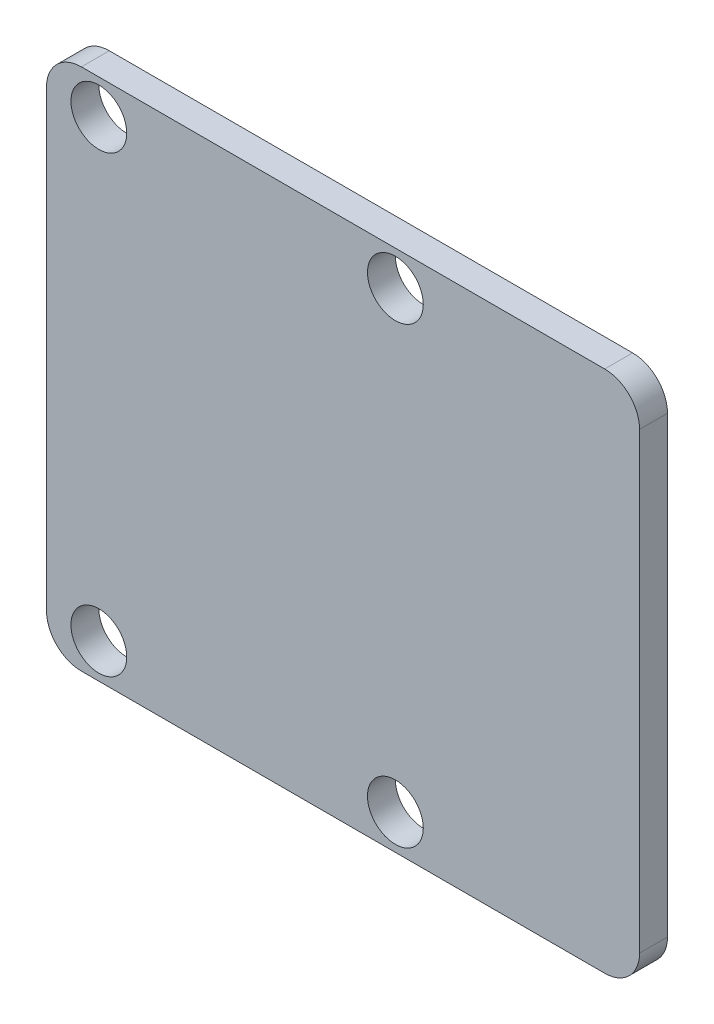
SolidWorks part; units mm, degrees
material "E-Glass Fiber"
ref_plane "Front Plane" through (0, 0, 0) normal (0, 0, 1) x (1, 0, 0)
ref_plane "Top Plane" through (0, 0, 0) normal (0, 1, 0) x (1, 0, 0)
ref_plane "Right Plane" through (0, 0, 0) normal (1, 0, 0) x (0, 0, -1)
sketch "Sketch1" plane through (0, 0, 0) normal (0, 0, 1) x (1, 0, 0)
  line L1 (-17, 15) -> (17, 15)
  line L2 (-17, 15) -> (-17, -15)
  line L3 (-17, -15) -> (17, -15)
  line L4 (17, 15) -> (17, -15)
  line L5 (-17, 15) -> (17, -15) construction
  line L6 (-17, -15) -> (17, 15) construction
  point P0 (0, 0)
  dimension "D1" = 34
  dimension "D2" = 30
extrude "Boss-Extrude1" add sketch "Sketch1" along normal blind 1.6
sketch "Sketch2" plane through (0, 0, 0) normal (0, 0, 1) x (1, 0, 0)
  line L0 (-14, 13) -> (3, 13) construction
  line L1 (-14, -13) -> (3, -13) construction
  line L2 (3, -13) -> (3, 13) construction
  line L3 (-14, 13) -> (-14, -13) construction
  line L4 (0, 0) -> (-14, 0) construction
  line L5 (-17, 15) -> (-17, -15) construction
  circle A0 centre (-14, 13) radius 1.6
  circle A1 centre (3, 13) radius 1.6
  circle A2 centre (3, -13) radius 1.6
  circle A3 centre (-14, -13) radius 1.6
  dimension "D1" = 3.2
  dimension "D2" = 3
  dimension "D3" = 17
  dimension "D4" = 26
extrude "Cut-Extrude1" cut sketch "Sketch2" along normal up to next
fillet "Fillet1" radius 2 4 edges at (17, 15, 0.8) (17, -15, 0.8) (-17, -15, 0.8) (-17, 15, 0.8)
